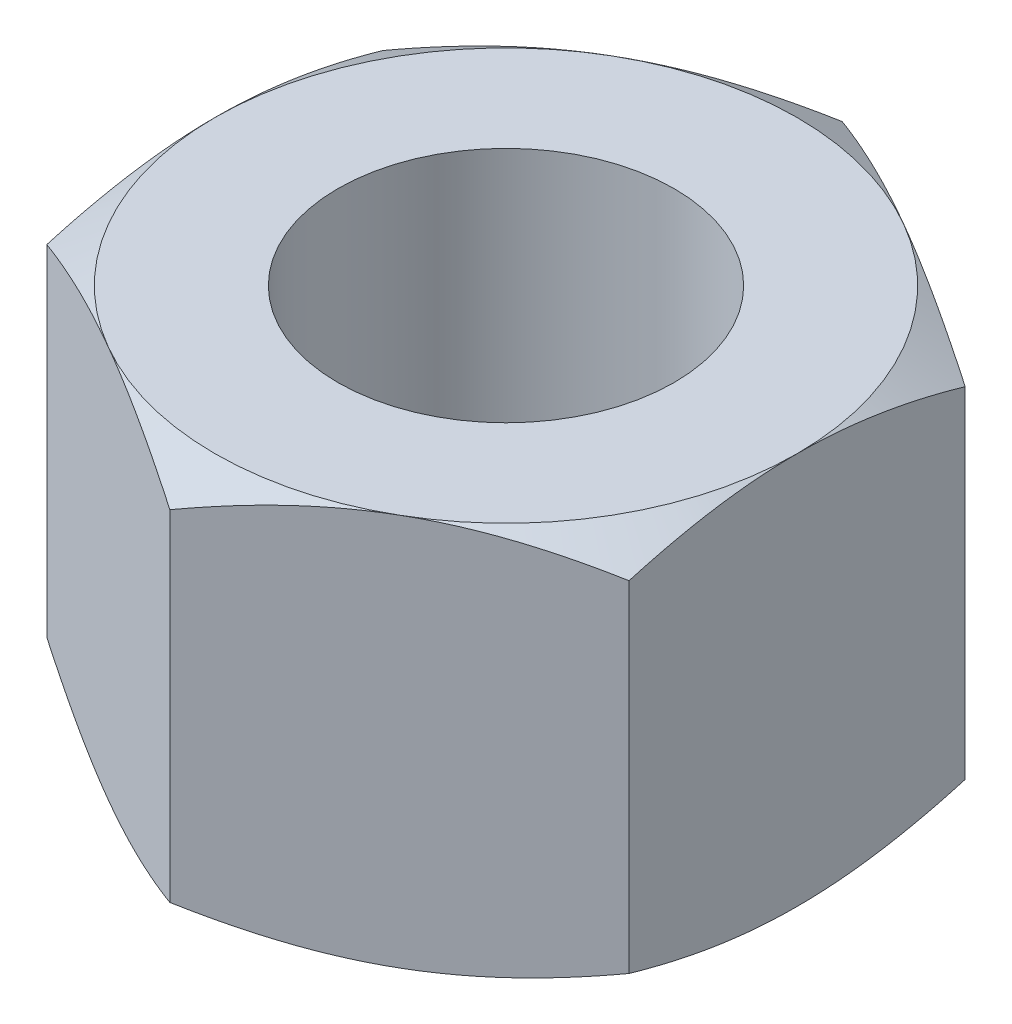
SolidWorks part; units mm, degrees
ref_plane "Front Plane" through (0, 0, 0) normal (0, 0, 1) x (1, 0, 0)
ref_plane "Top Plane" through (0, 0, 0) normal (0, 1, 0) x (1, 0, 0)
ref_plane "Right Plane" through (0, 0, 0) normal (1, 0, 0) x (0, 0, -1)
sketch "Sketch1" plane through (0, 0, 0) normal (0, 1, 0) x (1, 0, 0)
  line L1 (0, 30) -> (-25.9808, 15)
  line L2 (-25.9808, 15) -> (-25.9808, -15)
  line L3 (-25.9808, -15) -> (0, -30)
  line L4 (0, -30) -> (25.9808, -15)
  line L5 (25.9808, -15) -> (25.9808, 15)
  line L6 (25.9808, 15) -> (0, 30)
  circle A0 centre (0, 0) radius 25.9808 construction
  circle A1 centre (0, 0) radius 15
  dimension "D2" = 30
  dimension "D1" = 30
extrude "Boss-Extrude1" add sketch "Sketch1" along normal mid plane 35
sketch "Sketch2" plane through (0, 17.5, 0) normal (0, 1, 0) x (1, 0, 0)
  circle A0 centre (0, 0) radius 25.9808
extrude "Cut-Extrude1" cut sketch "Sketch2" against normal mid plane 35 draft 60 flip side to cut
mirror "Mirror1" about plane through (0, 0, 0) normal (0, 1, 0) of "Cut-Extrude1"
